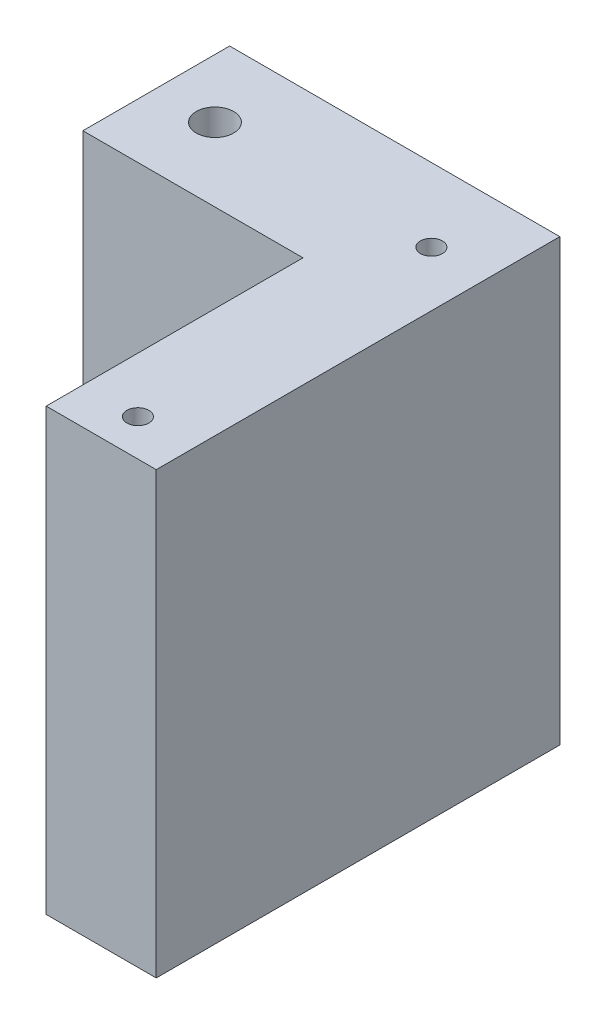
SolidWorks part; units mm, degrees
ref_plane "Front" through (0, 0, 0) normal (0, 0, 1) x (1, 0, 0)
ref_plane "Top" through (0, 0, 0) normal (0, 1, 0) x (1, 0, 0)
ref_plane "Right" through (0, 0, 0) normal (1, 0, 0) x (0, 0, -1)
sketch "Sketch1" plane through (0, 0, 0) normal (0, 1, 0) x (1, 0, 0)
  line L1 (-7.5, 27.5) -> (7.5, 27.5)
  line L2 (-7.5, 27.5) -> (-7.5, -27.5)
  line L3 (-7.5, -27.5) -> (7.5, -27.5)
  line L4 (7.5, 27.5) -> (7.5, -27.5)
  line L5 (-7.5, 27.5) -> (7.5, -27.5) construction
  line L6 (-7.5, -27.5) -> (7.5, 27.5) construction
  line L7 (-7.5, 27.5) -> (-37.5, 27.5)
  line L8 (-7.5, 27.5) -> (-7.5, 7.5)
  line L9 (-7.5, 7.5) -> (-37.5, 7.5)
  line L10 (-37.5, 27.5) -> (-37.5, 7.5)
  line L11 (-7.5, 27.5) -> (-37.5, 7.5) construction
  line L12 (-7.5, 7.5) -> (-37.5, 27.5) construction
  circle A0 centre (0, 17.5) radius 1.5
  circle A1 centre (0, -22.5) radius 1.5
  circle A3 centre (-29.5, 17.5) radius 2.55
  point P0 (0, 0)
  point P15 (-22.5, 17.5)
  dimension "D3" = 3
  dimension "D4" = 3
  dimension "D5" = 40
  dimension "D9" = 5.1
  dimension "D10" = 8
  dimension "D1" = 55
  dimension "D2" = 15
  dimension "D6" = 10
  dimension "D7" = 30
  dimension "D8" = 20
extrude "Boss-Extrude1" add sketch "Sketch1" along normal blind 60 contours L4 L1 L2 L3 A1 A0 | L7 L10 L9 L2 A3
sketch "Sketch2" plane through (0, 0, -27.5) normal (0, 0, -1) x (-1, 0, 0)
  line L0 (-7.5, 60) -> (-7.5, 0) construction
  circle A0 centre (22.5, 5) radius 2.5
  dimension "D2" = 5
  dimension "D3" = 5
  dimension "D5" = 30
extrude "Cut-Extrude1" cut sketch "Sketch2" against normal blind 20
